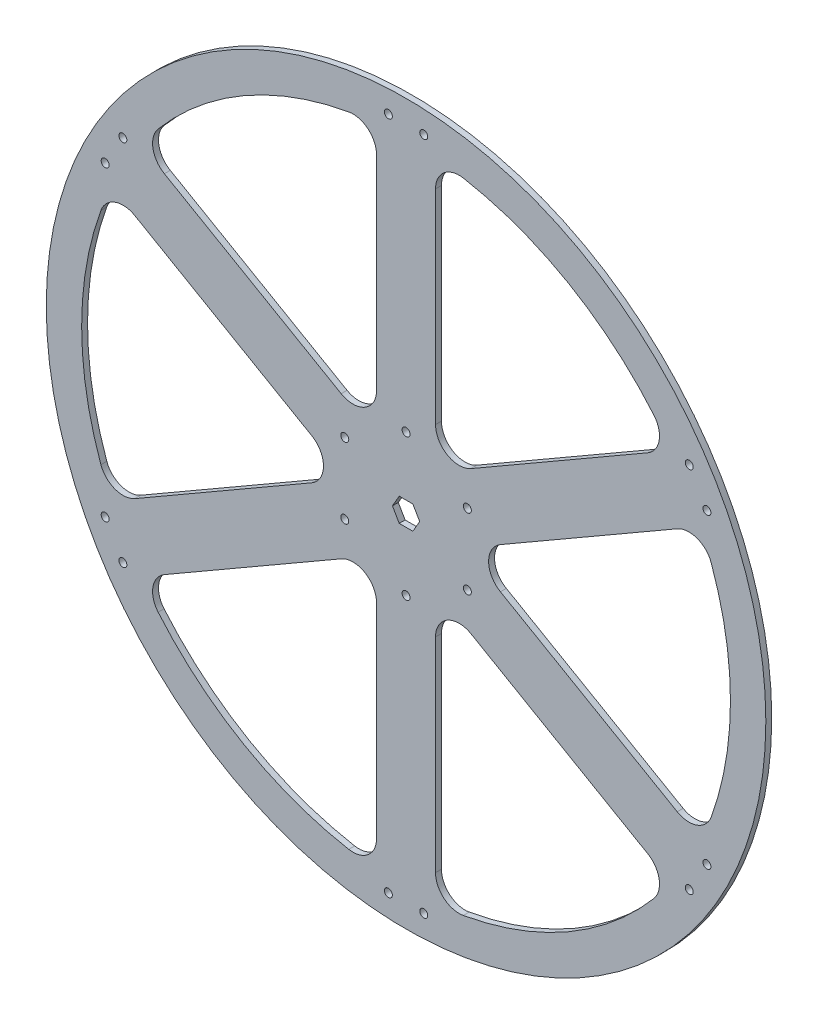
SolidWorks part; units mm, degrees
ref_plane "Front Plane" through (0, 0, 0) normal (0, 0, 1) x (1, 0, 0)
ref_plane "Top Plane" through (0, 0, 0) normal (0, 1, 0) x (1, 0, 0)
ref_plane "Right Plane" through (0, 0, 0) normal (1, 0, 0) x (0, 0, -1)
sketch "Sketch1" plane through (0, 0, 0) normal (0, 0, 1) x (1, 0, 0)
  line L1 (7.3323, 0) -> (3.6662, 6.35)
  line L2 (3.6662, 6.35) -> (-3.6662, 6.35)
  line L3 (-3.6662, 6.35) -> (-7.3323, 0)
  line L4 (-7.3323, 0) -> (-3.6662, -6.35)
  line L5 (-3.6662, -6.35) -> (3.6662, -6.35)
  line L6 (3.6662, -6.35) -> (7.3323, 0)
  circle A0 centre (0, 0) radius 193.675
  circle A2 centre (0, 0) radius 33.3375
  circle A3 centre (0, 0) radius 174.625
  circle A4 centre (0, 0) radius 6.35 construction
  dimension "D1" = 387.35
  dimension "D2" = 12.7
  dimension "D3" = 66.675
  dimension "D4" = 19.05
extrude "Boss-Extrude1" add sketch "Sketch1" along normal blind 3.175
sketch "Sketch2" plane through (0, 0, 3.175) normal (0, 0, 1) x (1, 0, 0)
  line L0 (0, 0) -> (0, 174.625) construction
  line L1 (15.875, 49.4934) -> (15.875, 159.3837)
  line L2 (-15.875, 49.4934) -> (-15.875, 159.3837)
  line L3 (15.875, 0) -> (15.875, 174.625) construction
  line L4 (-15.875, 0) -> (-15.875, 174.625) construction
  line L5 (34.925, 38.4948) -> (130.0929, 93.44)
  line L6 (50.8, 10.9985) -> (145.9679, 65.9437)
  line L7 (50.8, -10.9985) -> (145.9679, -65.9437)
  line L8 (34.925, -38.4948) -> (130.0929, -93.44)
  line L9 (15.875, -49.4934) -> (15.875, -159.3837)
  line L10 (-15.875, -49.4934) -> (-15.875, -159.3837)
  line L11 (-34.925, -38.4948) -> (-130.0929, -93.44)
  line L12 (-50.8, -10.9985) -> (-145.9679, -65.9437)
  line L13 (-50.8, 10.9985) -> (-145.9679, 65.9437)
  line L14 (-34.925, 38.4948) -> (-130.0929, 93.44)
  line L15 (7.3323, 0) -> (3.6662, 6.35) construction
  line L16 (3.6662, -6.35) -> (7.3323, 0) construction
  line L17 (-3.6662, -6.35) -> (3.6662, -6.35) construction
  line L18 (-7.3323, 0) -> (-3.6662, -6.35) construction
  line L19 (-3.6662, 6.35) -> (-7.3323, 0) construction
  line L20 (3.6662, 6.35) -> (-3.6662, 6.35) construction
  line L21 (7.3323, 0) -> (3.6662, 6.35)
  line L22 (3.6662, -6.35) -> (7.3323, 0)
  line L23 (-3.6662, -6.35) -> (3.6662, -6.35)
  line L24 (-7.3323, 0) -> (-3.6662, -6.35)
  line L25 (-3.6662, 6.35) -> (-7.3323, 0)
  line L26 (3.6662, 6.35) -> (-3.6662, 6.35)
  line L27 (0, 0) -> (0, 174.625) construction
  circle A0 centre (0, 0) radius 174.625 construction
  arc A1 (-50.0133, 167.3098) -> (-30.8162, 171.8844) centre (0, 0) cw construction
  arc A2 (30.8162, 171.8844) -> (68.6917, 160.547) centre (0, 0) cw construction
  arc A3 (-30.8162, 171.8844) -> (-15.875, 159.3837) centre (-28.575, 159.3837) cw
  arc A4 (15.875, 159.3837) -> (30.8162, 171.8844) centre (28.575, 159.3837) cw
  arc A5 (-50.8, -10.9985) -> (-50.8, 10.9985) centre (-57.15, 0) ccw
  arc A7 (-15.875, -49.4934) -> (-34.925, -38.4948) centre (-28.575, -49.4934) ccw
  arc A11 (-30.8162, 171.8844) -> (30.8162, 171.8844) centre (0, 0) cw
  arc A14 (133.4482, 112.6298) -> (130.0929, 93.44) centre (123.7429, 104.4385) cw
  arc A15 (133.4482, 112.6298) -> (164.2644, 59.2546) centre (0, 0) cw
  arc A16 (145.9679, 65.9437) -> (164.2644, 59.2546) centre (152.3179, 54.9452) cw
  arc A20 (164.2644, -59.2546) -> (145.9679, -65.9437) centre (152.3179, -54.9452) cw
  arc A21 (164.2644, -59.2546) -> (133.4482, -112.6298) centre (0, 0) cw
  arc A22 (130.0929, -93.44) -> (133.4482, -112.6298) centre (123.7429, -104.4385) cw
  arc A26 (30.8162, -171.8844) -> (15.875, -159.3837) centre (28.575, -159.3837) cw
  arc A27 (30.8162, -171.8844) -> (-30.8162, -171.8844) centre (0, 0) cw
  arc A28 (-15.875, -159.3837) -> (-30.8162, -171.8844) centre (-28.575, -159.3837) cw
  arc A32 (-133.4482, -112.6298) -> (-130.0929, -93.44) centre (-123.7429, -104.4385) cw
  arc A33 (-133.4482, -112.6298) -> (-164.2644, -59.2546) centre (0, 0) cw
  arc A34 (-145.9679, -65.9437) -> (-164.2644, -59.2546) centre (-152.3179, -54.9452) cw
  arc A38 (-164.2644, 59.2546) -> (-145.9679, 65.9437) centre (-152.3179, 54.9452) cw
  arc A39 (-164.2644, 59.2546) -> (-133.4482, 112.6298) centre (0, 0) cw
  arc A40 (-130.0929, 93.44) -> (-133.4482, 112.6298) centre (-123.7429, 104.4385) cw
  arc A43 (34.925, -38.4948) -> (15.875, -49.4934) centre (28.575, -49.4934) ccw
  arc A44 (50.8, 10.9985) -> (50.8, -10.9985) centre (57.15, 0) ccw
  arc A45 (15.875, 49.4934) -> (34.925, 38.4948) centre (28.575, 49.4934) ccw
  arc A46 (-15.875, 49.4934) -> (-34.925, 38.4948) centre (-28.575, 49.4934) cw
  point P20 (15.875, 173.9019)
  point P47 (0, 0)
  point P55 (-2.3056, 1.8654)
  point P95 (0, 0)
  dimension "D3" = 12.7
  dimension "D4" = 12.7
  dimension "D1" = 15.875
  dimension "D2" = 15.875
  dimension "D5" = 6
extrude "Boss-Extrude2" add sketch "Sketch2" against normal blind 3.175
sketch "Sketch3" plane through (0, 0, 3.175) normal (0, 0, 1) x (1, 0, 0)
  circle A0 centre (0, 0) radius 38.1 construction
  circle A1 centre (0, 38.1) radius 2.1527
  circle A2 centre (32.9956, 19.05) radius 2.1526
  circle A3 centre (32.9956, -19.05) radius 2.1527
  circle A4 centre (0, -38.1) radius 2.1527
  circle A5 centre (-32.9956, -19.05) radius 2.1527
  circle A6 centre (-32.9956, 19.05) radius 2.1527
  point P5 (0, 0)
  point P6 (-2.6908, 1.805)
  point P18 (0, 0)
  dimension "D1" = 4.3053
  dimension "D2" = 76.2
  dimension "D3" = 6
extrude "Cut-Extrude1" cut sketch "Sketch3" against normal blind 3.175
sketch "Sketch4" plane through (0, 0, 3.175) normal (0, 0, 1) x (1, 0, 0)
  circle A0 centre (-9.5206, 181.5192) radius 2.1527
  circle A1 centre (9.5206, 181.5192) radius 2.1526
  arc A2 (9.5206, 181.5192) -> (-9.5206, 181.5192) centre (0, 0) ccw construction
  point P5 (0, 0)
  point P7 (0, 181.7688)
  dimension "D1" = 181.7688
  dimension "D3" = 4.3053
  dimension "D2" = 19.05
extrude "Cut-Extrude2" cut sketch "Sketch4" against normal blind 3.175
pattern_circular "CirPattern1" count 6 over 360 about axis through (0, 0, 0) along (0, 0, 1) of "Cut-Extrude2"
